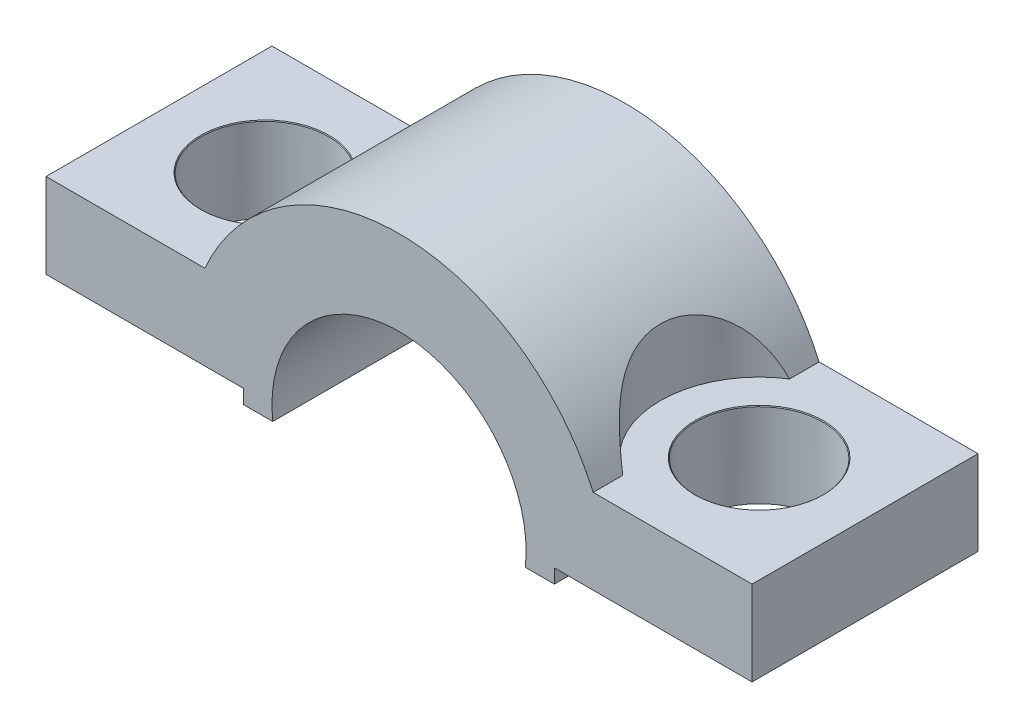
SolidWorks part; units mm, degrees
ref_plane "前视基准面" through (0, 0, 0) normal (0, 0, 1) x (1, 0, 0)
ref_plane "上视基准面" through (0, 0, 0) normal (0, 1, 0) x (1, 0, 0)
ref_plane "右视基准面" through (0, 0, 0) normal (1, 0, 0) x (0, 0, -1)
other "Configuration Table"
sketch "草图1" plane through (0, 0, 0) normal (0, 0, 1) x (1, 0, 0)
  line L0 (5.5, 0) -> (12.5, 0)
  line L1 (-12.5, 0) -> (-5.5, 0)
  line L2 (-12.5, 0) -> (-12.5, 3)
  line L3 (-12.5, 3) -> (-6.8739, 3)
  line L4 (12.5, 0) -> (12.5, 3)
  line L5 (4.0089, -0.5) -> (5.5, -0.5)
  line L6 (6.8739, 3) -> (12.5, 3)
  line L8 (-5.5, 0) -> (-5.5, -0.5)
  line L9 (-5.5, -0.5) -> (-4.0089, -0.5)
  line L10 (5.5, 0) -> (5.5, -0.5)
  arc A0 (6.8739, 3) -> (-6.8739, 3) centre (0, 0) ccw
  arc A1 (4.0089, -0.5) -> (-4.0089, -0.5) centre (0, 0) ccw
  dimension "D1" = 15
  dimension "D2" = 8.08
  dimension "D3" = 3
  dimension "D4" = 25
  dimension "D5" = 0.5
  dimension "D6" = 11
extrude "凸台-拉伸1" add sketch "草图1" along normal blind 8
sketch "草图2" plane through (0, 3, 0) normal (0, 1, 0) x (1, 0, 0)
  line L0 (-8.75, -4) -> (8.75, -4)
  line L1 (12.5, -8) -> (12.5, 0) construction
  point P2 (0, -4)
  point P7 (12.5, -4)
  dimension "D1" = 17.5
hole_wizard "M4 间隙孔1" positions "草图3" profile "草图5" hole size "M4" standard "GB"
sketch "草图3" plane through (0, 3, 0) normal (0, 1, 0) x (1, 0, 0)
  point P0 (-8.75, -4)
  point P3 (8.75, -4)
sketch "草图5" plane through (-8.75, 3, 4) normal (1, 0, 0) x (0, 0, 1)
  line L0 (0, 0) -> (0, 4.5019)
  line L1 (0, 4.5019) -> (2.25, 3.15)
  line L2 (2.25, 3.15) -> (2.25, 0.025)
  line L3 (2.25, 0.025) -> (2.275, 0)
  line L5 (2.275, 0) -> (0, 0)
  line L6 (-2.25, 0.025) -> (-2.275, 0) construction
  line L10 (0, 4.5019) -> (-2.25, 3.15) construction
  line L11 (0, -6.35) -> (0, 107.95) construction
  dimension "孔直径" = 4.5
  dimension "孔深度" = 3.15
  dimension "近端锥形沉头孔直径" = 4.55
  dimension "近端锥形沉头孔角度" = 90
  dimension "导头角度" = 118
sketch "草图6" plane through (0, 0, 8) normal (0, 0, 1) x (1, 0, 0)
  line L0 (-4.0089, -0.5) -> (-3.4641, -0.5)
  line L1 (3.4641, -0.5) -> (4.0089, -0.5)
  arc A0 (3.4641, -0.5) -> (-3.4641, -0.5) centre (0, 0) ccw
  arc A1 (4.0089, -0.5) -> (-4.0089, -0.5) centre (0, 0) ccw construction
  arc A2 (4.0089, -0.5) -> (-4.0089, -0.5) centre (0, 0) ccw
  dimension "D1" = 7
extrude "凸台-拉伸3" add sketch "草图6" against normal blind 4
sketch "草图7" plane through (0, 0, 0) normal (0, 0, -1) x (-1, 0, 0)
  circle A0 centre (0, 0) radius 4.5
  dimension "D1" = 9
extrude "切除-拉伸1" cut sketch "草图7" against normal blind 1
sketch "草图8" plane through (0, 3, 0) normal (0, 1, 0) x (1, 0, 0)
  circle A0 centre (-8.75, -4) radius 3.5
  dimension "D1" = 7
extrude "切除-拉伸2" cut sketch "草图8" along normal blind 10
mirror "镜向1" about plane through (0, 0, 0) normal (1, 0, 0) of "切除-拉伸2"
ref_plane "基准面1" through (-4.4721, -0.5, 1) normal (-0.1111, 0.9938, 0) x (0.9938, 0.1111, 0)
sketch "草图10" plane through (0, 0, 1) normal (0, 0, -1) x (-1, 0, 0)
  circle A0 centre (0, 0) radius 4.5
  dimension "D1" = 9
extrude "切除-拉伸3" cut sketch "草图10" against normal through all
